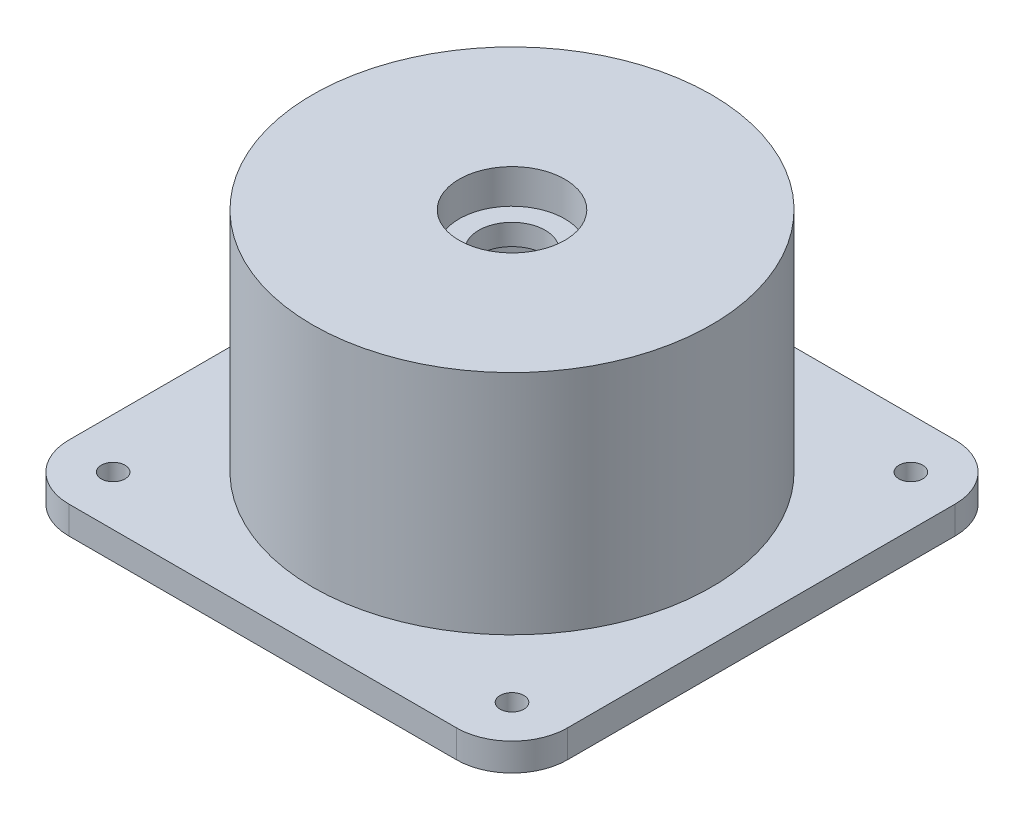
SolidWorks part; units mm, degrees
ref_plane "Front Plane" through (0, 0, 0) normal (0, 0, 1) x (1, 0, 0)
ref_plane "Top Plane" through (0, 0, 0) normal (0, 1, 0) x (1, 0, 0)
ref_plane "Right Plane" through (0, 0, 0) normal (1, 0, 0) x (0, 0, -1)
sketch "Sketch3" plane through (0, 0, 0) normal (0, 1, 0) x (1, 0, 0)
  line L1 (-35, 45) -> (35, 45)
  line L2 (-45, 35) -> (-45, -35)
  line L3 (-35, -45) -> (35, -45)
  line L4 (45, 35) -> (45, -35)
  line L5 (-45, 45) -> (45, -45) construction
  line L6 (-45, -45) -> (45, 45) construction
  arc A0 (-35, -45) -> (-45, -35) centre (-35, -35) cw
  arc A1 (35, -45) -> (45, -35) centre (35, -35) ccw
  arc A2 (35, 45) -> (45, 35) centre (35, 35) cw
  arc A3 (-35, 45) -> (-45, 35) centre (-35, 35) ccw
  circle A4 centre (-36, 36) radius 2.15
  circle A5 centre (36, 36) radius 2.15
  circle A6 centre (36, -36) radius 2.15
  circle A8 centre (-36, -36) radius 2.15
  point P0 (0, 0)
  dimension "D1" = 10
  dimension "D2" = 90
  dimension "D5" = 4.3
  dimension "D6" = 4.3
  dimension "D7" = 4.3
  dimension "D8" = 4.3
  dimension "D3" = 9
  dimension "D4" = 9
  dimension "D9" = 9
  dimension "D10" = 9
  dimension "D11" = 9
  dimension "D12" = 9
  dimension "D13" = 9
  dimension "D14" = 9
  dimension "D15" = 72
  dimension "D16" = 72
  dimension "D17" = 90
extrude "Boss-Extrude1" add sketch "Sketch3" along normal blind 5
sketch "Sketch4" plane through (0, 5, 0) normal (0, 1, 0) x (1, 0, 0)
  circle A0 centre (0, 0) radius 36
extrude "Boss-Extrude2" add sketch "Sketch4" along normal blind 41
sketch "Sketch5" plane through (0, 46, 0) normal (0, 1, 0) x (1, 0, 0)
  circle A0 centre (0, 0) radius 9.55
extrude "Cut-Extrude1" cut sketch "Sketch5" against normal blind 6.2
sketch "Sketch6" plane through (0, 0, 0) normal (0, -1, 0) x (1, 0, 0)
  circle A0 centre (0, 0) radius 32
extrude "Cut-Extrude2" cut sketch "Sketch6" against normal blind 36
sketch "Sketch8" plane through (0, 39.8, 0) normal (0, 1, 0) x (1, 0, 0)
  circle A0 centre (0, 0) radius 6
extrude "Cut-Extrude3" cut sketch "Sketch8" against normal through all
